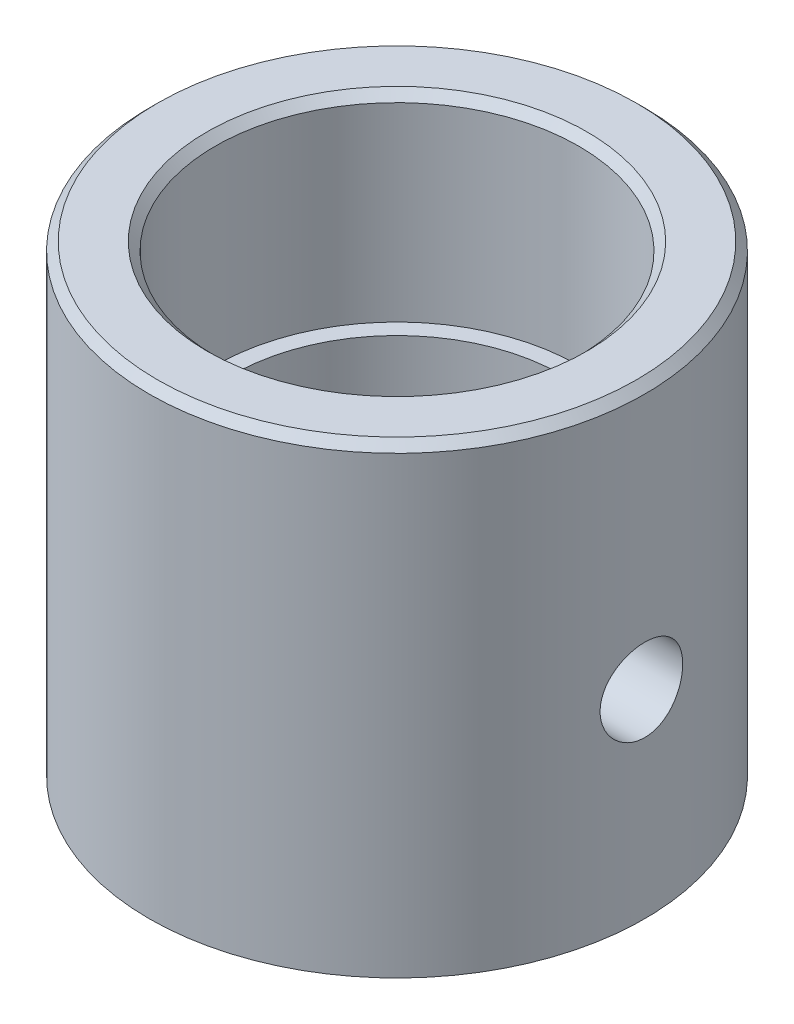
SolidWorks part; units mm, degrees
ref_plane "Front Plane" through (0, 0, 0) normal (0, 0, 1) x (1, 0, 0)
ref_plane "Top Plane" through (0, 0, 0) normal (0, 1, 0) x (1, 0, 0)
ref_plane "Right Plane" through (0, 0, 0) normal (1, 0, 0) x (0, 0, -1)
sketch "Sketch1" plane through (0, 0, 0) normal (0, 1, 0) x (1, 0, 0)
  circle A0 centre (0, 0) radius 15
  dimension "D1" = 30
extrude "Boss-Extrude1" add sketch "Sketch1" along normal blind 28
sketch "Sketch2" plane through (0, 28, 0) normal (0, 1, 0) x (1, 0, 0)
  circle A0 centre (0, 0) radius 10
  dimension "D1" = 20
extrude "Cut-Extrude1" cut sketch "Sketch2" against normal blind 27
sketch "Sketch3" plane through (0, 28, 0) normal (0, 1, 0) x (1, 0, 0)
  circle A0 centre (0, 0) radius 11
  dimension "D1" = 22
extrude "Cut-Extrude2" cut sketch "Sketch3" against normal blind 12
sketch "Sketch4" plane through (0, 0, 0) normal (1, 0, 0) x (0, 0, -1)
  line L0 (15, 28) -> (-15, 28) construction
  circle A0 centre (0, 12) radius 2.5
  dimension "D1" = 5
  dimension "D2" = 16
extrude "Cut-Extrude3" cut sketch "Sketch4" against normal mid plane 62
chamfer "Chamfer1" distance 0.5 angle 45 2 edges at (0, 28, 15) (0, 28, 11)
